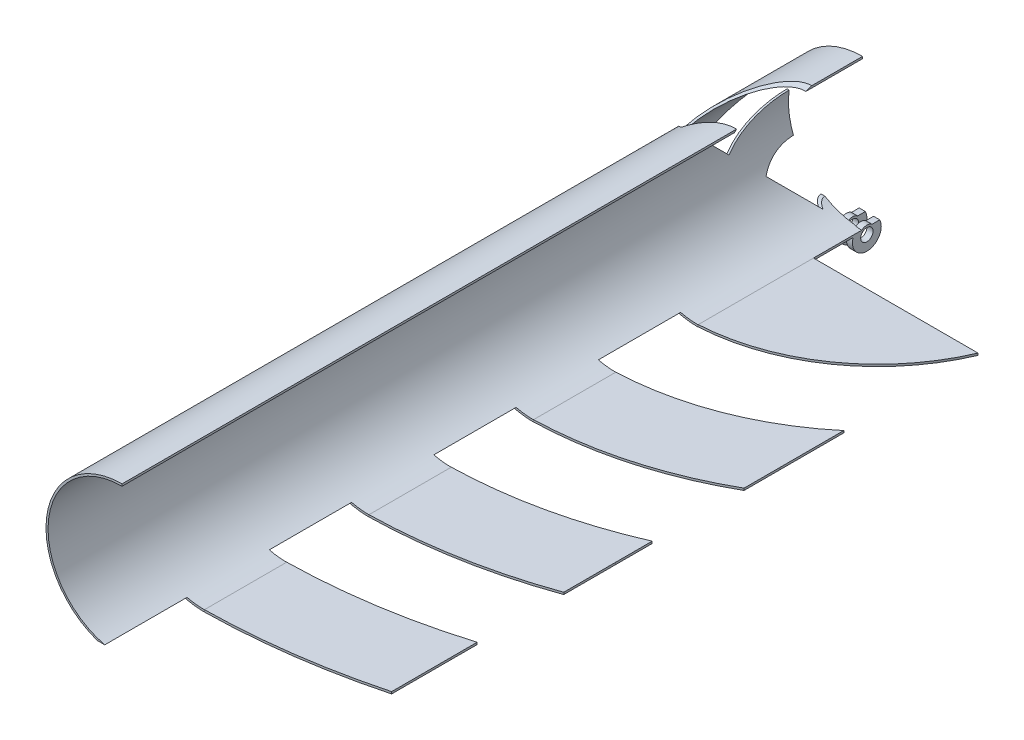
SolidWorks part; units mm, degrees
ref_plane "前视基准面" through (0, 0, 0) normal (0, 0, 1) x (1, 0, 0)
ref_plane "上视基准面" through (0, 0, 0) normal (0, 1, 0) x (1, 0, 0)
ref_plane "右视基准面" through (0, 0, 0) normal (1, 0, 0) x (0, 0, -1)
sketch "草图1" plane through (0, 0, 0) normal (0, 0, 1) x (1, 0, 0)
  circle A0 centre (0, 0) radius 18
  circle A1 centre (0, 0) radius 18.5
extrude "凸台-拉伸1" add sketch "草图1" along normal blind 180
sketch "草图2" plane through (0, 0, 0) normal (0, 0, -1) x (-1, 0, 0)
  line L0 (0, 0) -> (6.0887, 0)
  line L1 (0, 0) -> (0, 9.004)
sketch "草图3" plane through (0, 0, 180) normal (0, 0, 1) x (1, 0, 0)
  line L0 (0, 0) -> (-6.0887, 0)
  line L1 (0, 0) -> (0, 9.004)
ref_plane "基准面1" through (0, 0, 0) normal (1, 0, 0) x (0, 0, -1)
sketch "草图4" plane through (0, 0, 0) normal (1, 0, 0) x (0, 0, -1)
  line L0 (-2.1213, -16.3787) -> (-8.4853, -10.0147)
  line L1 (-23.7447, 23.2155) -> (0, 23.2155)
  line L2 (0, 23.2155) -> (0, 20.5)
  line L3 (0, -6.5) -> (0, -15.5)
  line L4 (-14.8492, -3.6508) -> (-21.2132, 2.7132)
  line L5 (0, 11.5) -> (0, 2.5)
  line L6 (-27.5772, 9.0772) -> (-33.9411, 15.4411)
  arc A0 (0, -15.5) -> (-2.1213, -16.3787) centre (0, -18.5) ccw
  arc A1 (0, -6.5) -> (-8.4853, -10.0147) centre (0, -18.5) ccw
  arc A2 (0, 2.5) -> (-14.8492, -3.6508) centre (0, -18.5) ccw
  arc A3 (0, 11.5) -> (-21.2132, 2.7132) centre (0, -18.5) ccw
  arc A4 (0, 20.5) -> (-27.5772, 9.0772) centre (0, -18.5) ccw
  arc A5 (-23.7447, 23.2155) -> (-33.9411, 15.4411) centre (0, -18.5) ccw
extrude "切除-拉伸1" cut sketch "草图4" against normal mid plane 60
ref_plane "基准面2" through (0, 0, 0) normal (0, 1, 0) x (1, 0, 0)
sketch "草图6" plane through (0, 0, 0) normal (0, 0, -1) x (-1, 0, 0)
  arc A0 (-10.0995, -15.5) -> (10.0995, -15.5) centre (0, 0) ccw construction
  point P0 (0, -18.5)
ref_point "点1"
ref_plane "基准面3" through (0, -18.5, 0) normal (0, 1, 0) x (1, 0, 0)
sketch "草图5" plane through (0, 0, 0) normal (1, 0, 0) x (0, 0, -1)
  line L2 (-0.1901, -18) -> (-2.0721, -18)
  line L3 (2.3114, -18) -> (4.1934, -18)
  arc A2 (-2.0721, -18) -> (4.1934, -18) centre (1.0607, -19.5607) ccw
  arc A5 (2.3114, -18) -> (-0.1901, -18) centre (1.0607, -19.5607) ccw
  circle A6 centre (1.0607, -19.5607) radius 1.5
  point P0 (0, -18)
extrude "凸台-拉伸2" add sketch "草图5" along normal mid plane 10
ref_plane "基准面4" through (3.5, 0, 0) normal (1, 0, 0) x (0, 0, -1)
sketch "草图8" plane through (3.5, 0, 0) normal (1, 0, 0) x (0, 0, -1)
  line L0 (-0.1901, -18) -> (-2.0721, -18)
  line L1 (2.3114, -18) -> (4.1934, -18)
  circle A0 centre (1.0607, -19.5607) radius 1.5
  arc A1 (2.3114, -18) -> (-0.1901, -18) centre (1.0607, -19.5607) ccw
  arc A2 (-2.0721, -18) -> (4.1934, -18) centre (1.0607, -19.5607) ccw
extrude "切除-拉伸2" cut sketch "草图8" against normal blind 2
ref_plane "基准面5" through (-1.5, 0, 0) normal (1, 0, 0) x (0, 0, -1)
sketch "草图9" plane through (-1.5, 0, 0) normal (1, 0, 0) x (0, 0, -1)
  line L0 (-2.0721, -18) -> (-0.1901, -18)
  line L1 (2.3114, -18) -> (4.1934, -18)
  circle A0 centre (1.0607, -19.5607) radius 1.5
  arc A1 (2.3114, -18) -> (-0.1901, -18) centre (1.0607, -19.5607) ccw
  arc A2 (-2.0721, -18) -> (4.1934, -18) centre (1.0607, -19.5607) ccw
extrude "切除-拉伸3" cut sketch "草图9" against normal blind 2
sketch "草图12" plane through (0, 0, 0) normal (0, 0, -1) x (-1, 0, 0)
  line L0 (0, 24.3371) -> (0, -25.7639)
  line L1 (0, 24.3371) -> (-21.5435, 24.3371)
  line L2 (0, -25.7639) -> (-21.5435, -25.7639)
  line L3 (-21.5435, 24.3371) -> (-21.5435, -25.7639)
  line L4 (0, 25.0366) -> (0, -25.0366) construction
extrude "切除-拉伸4" cut sketch "草图12" against normal mid plane 402
sketch "草图13" plane through (0, 0, 0) normal (1, 0, 0) x (0, 0, -1)
  line L0 (-100, -18.5) -> (-120, -18.5)
  line L1 (-2.2748, -18.5) -> (-180, -18.5) construction
  line L2 (-60, -18.5) -> (-80, -18.5)
  line L3 (-60, -18.5) -> (-60, -18)
  line L4 (-80, -18.5) -> (-80, -18)
  line L5 (-60, -18) -> (-80, -18)
  line L6 (-100, -18.5) -> (-100, -18)
  line L7 (-100, -18) -> (-120, -18)
  line L8 (-120, -18.5) -> (-120, -18)
  line L9 (-60, -18.5) -> (-100, -18.5) construction
  line L10 (-140, -18.5) -> (-160, -18.5)
  line L11 (-140, -18.5) -> (-140, -18)
  line L12 (-140, -18) -> (-160, -18)
  line L13 (-160, -18.5) -> (-160, -18)
  dimension "D1" = 3
  dimension "D2" = 20
  dimension "D3" = 0.5
  dimension "D4" = 40
extrude "凸台-拉伸3" add sketch "草图13" along normal blind 40
sketch "草图14" plane through (0, 0, 0) normal (1, 0, 0) x (0, 0, -1)
  line L0 (-80, -18.5) -> (-100, -18.5)
  line L1 (-2.2748, -18.5) -> (-60, -18.5) construction
  line L2 (-40, -18.5) -> (-60, -18.5)
  line L3 (-40, -18.5) -> (-40, -17.5)
  line L4 (-60, -18.5) -> (-60, -17.5)
  line L5 (-40, -17.5) -> (-60, -17.5)
  line L6 (-80, -18.5) -> (-80, -17.5)
  line L7 (-80, -17.5) -> (-100, -17.5)
  line L8 (-100, -18.5) -> (-100, -17.5)
  line L9 (-120, -18.5) -> (-140, -18.5)
  line L10 (-120, -18.5) -> (-120, -17.5)
  line L11 (-120, -17.5) -> (-140, -17.5)
  line L12 (-140, -18.5) -> (-140, -17.5)
  line L13 (-160, -18.5) -> (-180, -18.5)
  line L14 (-160, -18.5) -> (-160, -17.5)
  line L15 (-160, -17.5) -> (-180, -17.5)
  line L16 (-180, -18.5) -> (-180, -17.5)
  line L17 (-40, -18.5) -> (-80, -18.5) construction
  dimension "D1" = 4
  dimension "D2" = 20
  dimension "D3" = 1
  dimension "D4" = 40
extrude "切除-拉伸5" cut sketch "草图14" against normal blind 40
sketch "草图16" plane through (0, -18.5, 0) normal (0, -1, 0) x (1, 0, 0)
  line L0 (39.9987, 44.5573) -> (39.999, 68.7952)
  line L2 (0, -25.0366) -> (0, 25.0366) construction
  line L3 (0, 11.92) -> (0, 39.9323)
  line L4 (0, 11.92) -> (39.9983, 11.92)
  line L6 (0, 159.9812) -> (0, 139.9786)
  line L7 (39.9992, 91.1255) -> (39.9995, 112.6286)
  line L8 (0, 79.9637) -> (0, 59.9528)
  line L9 (39.9997, 133.6864) -> (39.9999, 154.4742)
  line L10 (0, 119.9752) -> (0, 99.9706)
  arc A0 (39.9987, 44.5573) -> (0, 59.9528) centre (-2.5, -6.2) ccw
  arc A1 (39.9983, 11.92) -> (0, 39.9323) centre (-2.5, -6.2) ccw
  arc A2 (39.999, 68.7952) -> (0, 79.9637) centre (-2.5, -6.2) ccw
  arc A3 (39.9992, 91.1255) -> (0, 99.9706) centre (-2.5, -6.2) ccw
  arc A4 (39.9995, 112.6286) -> (0, 119.9752) centre (-2.5, -6.2) ccw
  arc A5 (39.9997, 133.6864) -> (0, 139.9786) centre (-2.5, -6.2) ccw
  arc A6 (39.9999, 154.4742) -> (0, 159.9812) centre (-2.5, -6.2) ccw
extrude "凸台-拉伸4" add sketch "草图16" against normal blind 0.5
sketch "草图20" plane through (0, -18.5, 0) normal (0, -1, 0) x (1, 0, 0)
  line L0 (40, 80) -> (40, 68.7946)
  line L2 (40, 80) -> (0, 80)
  line L4 (0, 80) -> (0, 79.9637)
  arc A0 (40, 68.7946) -> (0, 79.9637) centre (-2.5, -6.2) ccw
extrude "切除-拉伸25" cut sketch "草图20" against normal blind 0.5
sketch "草图22" plane through (0, -18.5, 0) normal (0, -1, 0) x (1, 0, 0)
  line L0 (40, 120) -> (40, 112.6284)
  line L2 (40, 120) -> (0, 120)
  line L3 (0, 120) -> (0, 119.9752)
  arc A0 (40, 112.6284) -> (0, 119.9752) centre (-2.5, -6.2) ccw
extrude "切除-拉伸26" cut sketch "草图22" against normal blind 0.5
sketch "草图23" plane through (0, -18.5, 0) normal (0, -1, 0) x (1, 0, 0)
  line L0 (40, 160) -> (40, 154.4742)
  line L2 (40, 160) -> (0, 160)
  line L3 (0, 160) -> (0, 159.9812)
  arc A0 (40, 154.4742) -> (0, 159.9812) centre (-2.5, -6.2) ccw
extrude "切除-拉伸27" cut sketch "草图23" against normal blind 0.5
